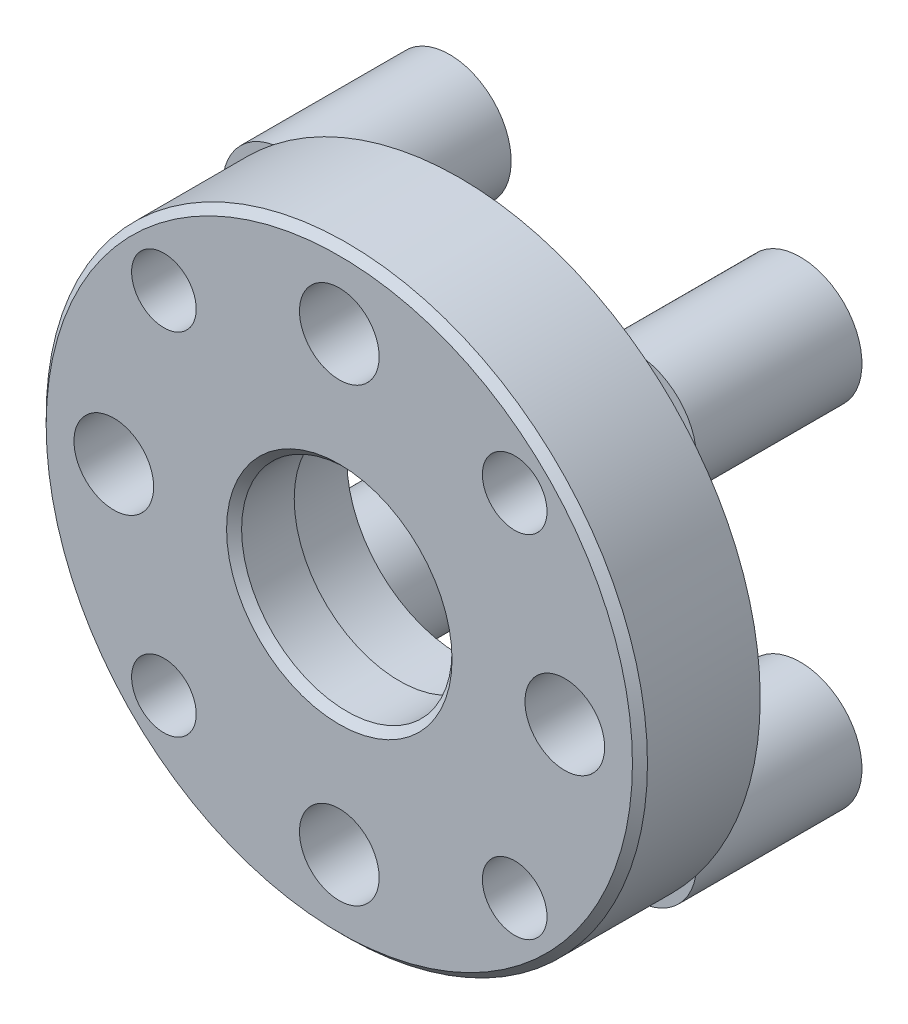
SolidWorks part; units mm, degrees
material "ABS"
ref_plane "Front Plane" through (0, 0, 0) normal (0, 0, 1) x (1, 0, 0)
ref_plane "Top Plane" through (0, 0, 0) normal (0, 1, 0) x (1, 0, 0)
ref_plane "Right Plane" through (0, 0, 0) normal (1, 0, 0) x (0, 0, -1)
ref_plane "Output Plane" through (0, 0, 25.2347) normal (0, 0, -1) x (-1, 0, 0)
sketch "CYC Output Sketch" plane through (0, 0, 25.2347) normal (0, 0, 1) x (1, 0, 0)
  line L1 (11.6673, 11.6673) -> (-11.6673, 11.6673) construction
  line L2 (-11.6673, 11.6673) -> (-11.6673, -11.6673) construction
  line L3 (-11.6673, -11.6673) -> (11.6673, -11.6673) construction
  line L4 (11.6673, -11.6673) -> (11.6673, 11.6673) construction
  circle A0 centre (0, 0) radius 16.5 construction
sketch "Sketch3" plane through (0, 0, 25.2347) normal (0, 0, -1) x (-1, 0, 0)
  circle A0 centre (-11.6673, 11.6673) radius 4
  circle A1 centre (11.6673, 11.6673) radius 4
  circle A2 centre (11.6673, -11.6673) radius 4
  circle A3 centre (-11.6673, -11.6673) radius 4
  dimension "D1" = 8
extrude "Boss-Extrude1" add sketch "Sketch3" along normal blind 11
sketch "Sketch6" plane through (0, 0, 25.2347) normal (0, 0, 1) x (1, 0, 0)
  arc A0 (10.6823, 16.9082) -> (-16.9082, 10.6823) centre (0, 0) ccw
  arc A18 (16.9082, -10.6823) -> (10.6823, 16.9082) centre (0, 0) ccw
  arc A19 (-10.6823, -16.9082) -> (16.9082, -10.6823) centre (0, 0) ccw
  arc A20 (-16.9082, 10.6823) -> (-10.6823, -16.9082) centre (0, 0) ccw
  circle A23 centre (0, 0) radius 7.5
  dimension "D2" = 40
  dimension "D1" = 15
extrude "Boss-Extrude6" add sketch "Sketch6" along normal blind 8 contours A23 | A0 A20 A19 A18
sketch "Sketch8" plane through (0, 0, 33.2347) normal (0, 0, 1) x (1, 0, 0)
  line L0 (0, 0) -> (11.6673, 11.6673) construction
  line L1 (0, 0) -> (16.5, 0) construction
  circle A0 centre (0, 0) radius 16.5 construction
  circle A1 centre (11.6673, 11.6673) radius 1.6
  circle A2 centre (11.6673, -11.6673) radius 1.6
  circle A3 centre (-11.6673, -11.6673) radius 1.6
  circle A4 centre (-11.6673, 11.6673) radius 1.6
  point P16 (0, 0)
  dimension "D1" = 33
  dimension "D2" = 45
  dimension "D3" = 3.2
  dimension "D4" = 4
extrude "Cut-Extrude1" cut sketch "Sketch8" against normal through all
sketch "Sketch9" plane through (0, 0, 14.2347) normal (0, 0, 1) x (1, 0, 0)
  circle A0 centre (11.6673, 11.6673) radius 3
  circle A1 centre (11.6673, -11.6673) radius 3
  circle A2 centre (-11.6673, -11.6673) radius 3
  circle A3 centre (-11.6673, 11.6673) radius 3
  point P12 (0, 0)
  dimension "D1" = 6
  dimension "D2" = 4
extrude "Cut-Extrude2" cut sketch "Sketch9" along normal blind 3 from surface at 0 starting at face at (13.2673, 11.6673, 14.2347)
sketch "Sketch10" plane through (0, 0, 14.2347) normal (0, 0, -1) x (-1, 0, 0)
  circle A0 centre (11.6673, 11.6673) radius 4.1
  circle A1 centre (11.6673, 11.6673) radius 4
  circle A2 centre (11.6673, -11.6673) radius 4
  circle A3 centre (11.6673, -11.6673) radius 4.1
  circle A4 centre (-11.6673, -11.6673) radius 4
  circle A5 centre (-11.6673, -11.6673) radius 4.1
  circle A6 centre (-11.6673, 11.6673) radius 4
  circle A7 centre (-11.6673, 11.6673) radius 4.1
  point P16 (0, 0)
  dimension "D1" = 8
  dimension "D2" = 8.2
  dimension "D3" = 4
extrude "Boss-Extrude8" add sketch "Sketch10" against normal blind 11
sketch "Sketch11" plane through (0, 0, 33.2347) normal (0, 0, 1) x (1, 0, 0)
  line L0 (0, 0) -> (0, 15) construction
  circle A0 centre (0, 15) radius 2.65
  circle A1 centre (15, 0) radius 2.65
  circle A2 centre (0, -15) radius 2.65
  circle A3 centre (-15, 0) radius 2.65
  circle A4 centre (-11.6673, 11.6673) radius 2.15
  circle A5 centre (11.6673, 11.6673) radius 2.15
  circle A6 centre (11.6673, -11.6673) radius 2.15
  circle A7 centre (-11.6673, -11.6673) radius 2.15
  point P13 (0, 0)
  dimension "D2" = 5.3
  dimension "D4" = 4.3
  dimension "D1" = 15
  dimension "D3" = 4
extrude "Cut-Extrude3" cut sketch "Sketch11" against normal blind 8
sketch "Sketch12" plane through (0, 0, 33.2347) normal (0, 0, 1) x (1, 0, 0)
  circle A0 centre (0, 0) radius 7.5
  circle A1 centre (0, 0) radius 7
  dimension "D1" = 15
  dimension "D2" = 14
extrude "Boss-Extrude9" add sketch "Sketch12" against normal blind 4
chamfer "Chamfer1" distance 0.5 angle 45 2 edges at (7, 0, 33.2347) (20, 0, 33.2347)
equation "\"RingPinShaft\"= 5.05"
equation "\"CenterBearingOut\"=32.00"
equation "\"RingPostIn\"=5.15"
equation "\"CamBearingOut\"=15.1"
equation "\"DiskOutputShaft\"=10.1"
equation "\"CenterShaft\"=25.2"
equation "\"Eccentricity\"=2"
equation "\"CycCamShaft\"=10.05"
equation "\"D2@Sketch6\"=\"OutputBearing\""
equation "\"OutputBearing\"=40"
